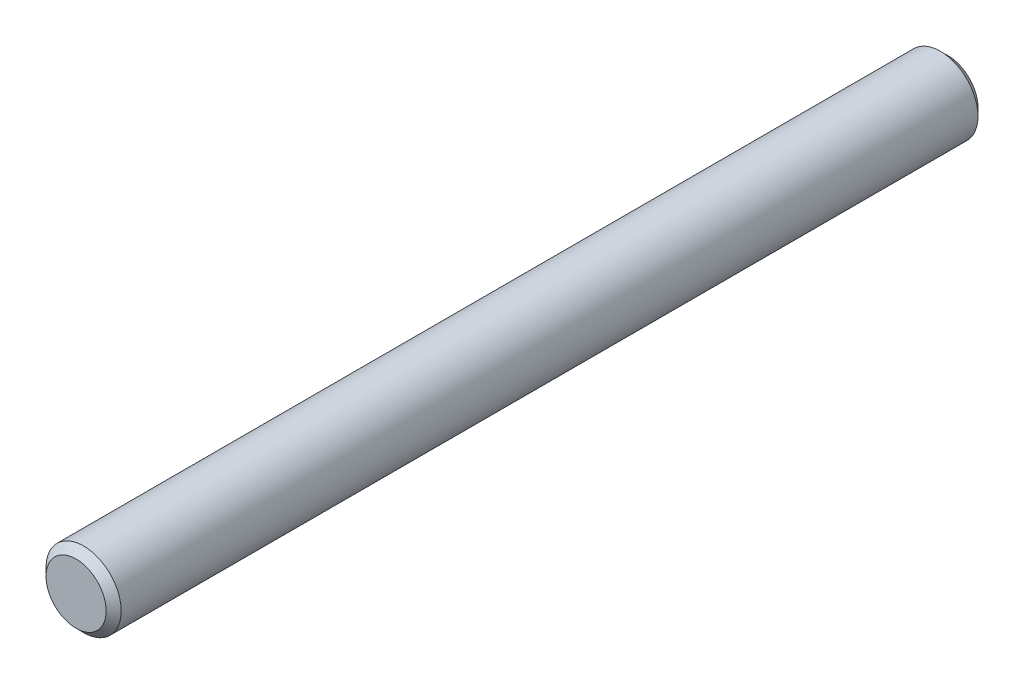
SolidWorks part; units mm, degrees
ref_plane "Alzado" through (0, 0, 0) normal (0, 0, 1) x (1, 0, 0)
ref_plane "Planta" through (0, 0, 0) normal (0, 1, 0) x (1, 0, 0)
ref_plane "Vista lateral" through (0, 0, 0) normal (1, 0, 0) x (0, 0, -1)
sketch "Croquis1" plane through (0, 0, 0) normal (0, 0, 1) x (1, 0, 0)
  circle A0 centre (0, 0) radius 2.5
  dimension "D1" = 5
extrude "Saliente-Extruir1" add sketch "Croquis1" against normal blind 58
chamfer "Chaflán1" distance 0.5 angle 45 2 edges at (2.5, 0, -58) (2.5, 0, 0)
